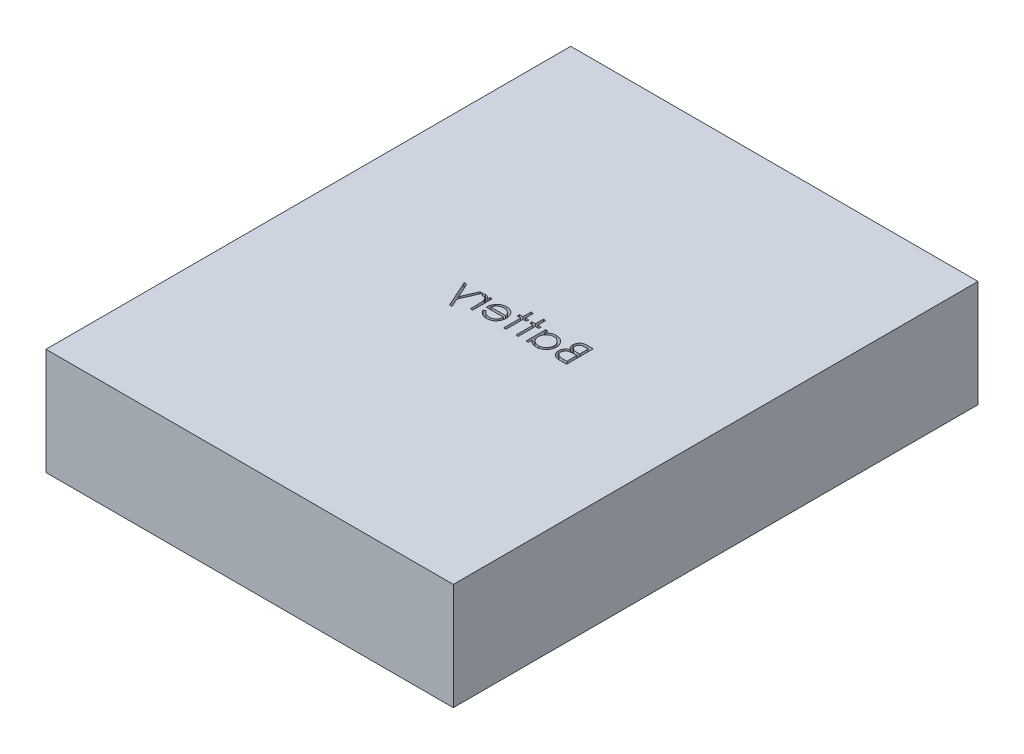
SolidWorks part; units mm, degrees
ref_plane "Front Plane" through (0, 0, 0) normal (0, 0, 1) x (1, 0, 0)
ref_plane "Top Plane" through (0, 0, 0) normal (0, 1, 0) x (1, 0, 0)
ref_plane "Right Plane" through (0, 0, 0) normal (1, 0, 0) x (0, 0, -1)
sketch "Sketch1" plane through (0, 0, 0) normal (0, 1, 0) x (1, 0, 0)
  line L1 (0, 0) -> (53.4, 0)
  line L2 (0, 0) -> (0, 68.8)
  line L3 (0, 68.8) -> (53.4, 68.8)
  line L4 (53.4, 0) -> (53.4, 68.8)
  dimension "D1" = 68.8
  dimension "D2" = 53.4
extrude "Boss-Extrude1" add sketch "Sketch1" along normal blind 14
sketch "Sketch2" plane through (0, 14, 0) normal (0, 1, 0) x (1, 0, 0)
  text T0 "Rasperry Pi"
extrude "Cut-Extrude1" [suppressed] cut sketch "Sketch2" against normal through all
sketch "Sketch3" plane through (0, 14, 0) normal (0, 1, 0) x (1, 0, 0)
  text T0 "arduino"
extrude "Cut-Extrude2" [suppressed] cut sketch "Sketch3" against normal blind 29
sketch "Sketch4" [suppressed] plane through (0, 24.4, 0) normal (0, 1, 0) x (1, 0, 0)
  text T0 "gps beacon"
extrude "Cut-Extrude3" [suppressed] cut sketch "Sketch4" against normal through all
sketch "Sketch5" [suppressed] plane through (0, 50, 0) normal (0, 1, 0) x (1, 0, 0)
  text T0 "GPS Modem"
extrude "Cut-Extrude4" [suppressed] cut sketch "Sketch5" against normal through all
sketch "Sketch6" [suppressed] plane through (0, 10, 0) normal (0, 1, 0) x (1, 0, 0)
  text T0 "Breadboard"
extrude "Cut-Extrude5" [suppressed] cut sketch "Sketch6" against normal through all
sketch "Sketch7" [suppressed] plane through (0, 50, 0) normal (0, 1, 0) x (1, 0, 0)
  text T0 "Motor Drive"
extrude "Cut-Extrude6" [suppressed] cut sketch "Sketch7" against normal through all
sketch "Sketch8" [suppressed] plane through (0, 24.4, 0) normal (0, 1, 0) x (1, 0, 0)
  text T0 "Motor"
extrude "Cut-Extrude7" [suppressed] cut sketch "Sketch8" against normal through all
sketch "Sketch9" [suppressed] plane through (0, 0, -50) normal (0, 0, -1) x (-1, 0, 0)
  line L1 (-24.4, 24.4) -> (0, 0) construction
  line L4 (-24.4, 0) -> (0, 0)
  line L5 (0, 0) -> (0, 24.4)
  line L6 (0, 24.4) -> (-24.4, 24.4)
  line L7 (-24.4, 24.4) -> (-24.4, 0)
  line L8 (-24.4, 0) -> (0, 0)
  line L9 (0, 0) -> (0, 24.4)
  line L10 (0, 24.4) -> (-24.4, 24.4)
  line L11 (-24.4, 24.4) -> (-24.4, 0)
  circle A0 centre (-12.2, 12.2) radius 2
  dimension "D1" = 0
extrude "Boss-Extrude2" [suppressed] add sketch "Sketch9" along normal blind 20 contours L1 A0 | A0 L1
shell "Shell1" [suppressed] thickness 1
sketch "Sketch10" plane through (0, 0, 0) normal (0, -1, 0) x (-1, 0, 0)
  text T0 "Battery"
extrude "Cut-Extrude8" cut sketch "Sketch10" against normal mid plane 30
